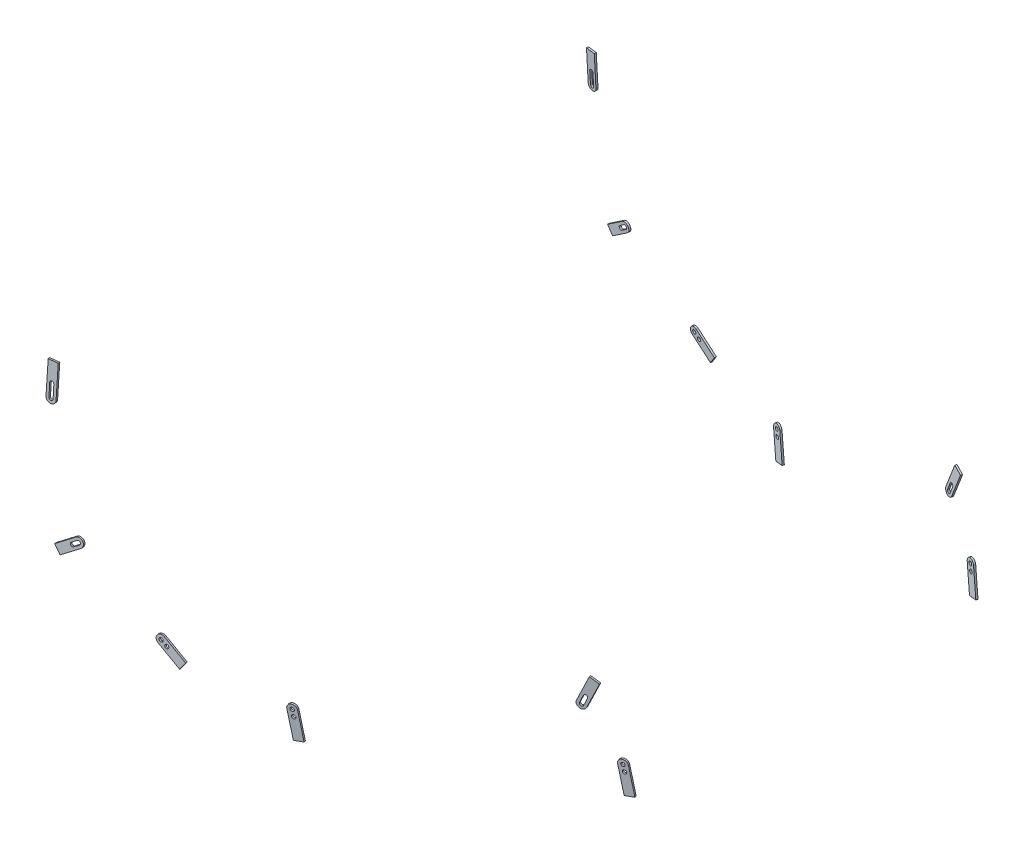
SolidWorks part; units mm, degrees
ref_plane "Front Plane" through (0, 0, 0) normal (0, 0, 1) x (1, 0, 0)
ref_plane "Top Plane" through (0, 0, 0) normal (0, 1, 0) x (1, 0, 0)
ref_plane "Right Plane" through (0, 0, 0) normal (1, 0, 0) x (0, 0, -1)
sketch3d "3DSketch1"
  line L0 (394.3882, 355.8329, 258.042) -> (773.7071, 652.4915, 190.2318) construction
  line L1 (773.7071, 652.4915, 190.2318) -> (658.3543, 555, 15) construction
  line L2 (394.3882, 355.8329, -258.042) -> (773.7071, 652.4915, -190.2318) construction
  line L3 (773.7071, 652.4915, -190.2318) -> (658.3543, 555, -15) construction
  line L4 (773.7071, 349.9436, 210) -> (-11.91, 362.141, 309.501) construction
  line L5 (-163, 610, 200) -> (-87.4986, 741.4827, 256.6073) construction
  line L6 (-68.7898, 625.9945, -300.6274) -> (-163, 610, -200) construction
  line L7 (-68.7898, 625.9945, 300.6274) -> (-68.7898, 625.9945, -300.6274) construction
  line L8 (-68.7898, 625.9945, 300.6274) -> (-163, 610, 200) construction
  line L9 (-163, 610, 200) -> (-163, 610, -200) construction
  line L10 (-163, 610, 200) -> (-163, 610, 230) construction
  line L11 (773.7071, 349.9436, -210) -> (-11.91, 362.141, -309.501) construction
  line L12 (-163, 610, -200) -> (-87.4986, 741.4827, -256.6073) construction
  line L13 (-163, 610, -200) -> (-163, 610, -230) construction
  line L14 (773.7071, 180, 150) -> (394.3882, 355.8329, 258.042) construction
  line L15 (200, 72.7, 300) -> (773.7071, 180, 150) construction
  line L16 (200, 72.7, 300) -> (394.3882, 355.8329, 258.042) construction
  line L17 (200, 72.7, -300) -> (394.3882, 355.8329, -258.042) construction
  line L18 (200, 72.7, -300) -> (773.7071, 180, -150) construction
  line L19 (773.7071, 180, -150) -> (394.3882, 355.8329, -258.042) construction
  line L20 (-100.891, 824.1527, 220.3063) -> (-100.891, 824.1527, -220.3063) construction
  line L21 (-176.299, 812.9937, 150) -> (-100.891, 824.1527, 220.3063) construction
  line L22 (-176.299, 812.9937, 150) -> (-176.299, 812.9937, -150) construction
  line L23 (-176.299, 812.9937, -150) -> (-100.891, 824.1527, -220.3063) construction
  line L24 (394.3882, 355.8329, 258.042) -> (773.7071, 652.4915, 190.2318)
  line L25 (773.7071, 652.4915, 190.2318) -> (658.3543, 555, 15)
  line L26 (394.3882, 355.8329, -258.042) -> (773.7071, 652.4915, -190.2318)
  line L27 (773.7071, 652.4915, -190.2318) -> (658.3543, 555, -15)
  line L28 (773.7071, 349.9436, 210) -> (-11.91, 362.141, 309.501)
  line L29 (-163, 610, 200) -> (-87.4986, 741.4827, 256.6073)
  line L30 (-68.7898, 625.9945, -300.6274) -> (-163, 610, -200)
  line L31 (-68.7898, 625.9945, 300.6274) -> (-68.7898, 625.9945, -300.6274)
  line L32 (-68.7898, 625.9945, 300.6274) -> (-163, 610, 200)
  line L33 (-163, 610, 200) -> (-163, 610, -200)
  line L34 (-163, 610, 200) -> (-163, 610, 230)
  line L35 (773.7071, 349.9436, -210) -> (-11.91, 362.141, -309.501)
  line L36 (-163, 610, -200) -> (-87.4986, 741.4827, -256.6073)
  line L37 (-163, 610, -200) -> (-163, 610, -230)
  line L38 (773.7071, 180, 150) -> (394.3882, 355.8329, 258.042)
  line L39 (200, 72.7, 300) -> (773.7071, 180, 150)
  line L40 (200, 72.7, 300) -> (394.3882, 355.8329, 258.042)
  line L41 (200, 72.7, -300) -> (394.3882, 355.8329, -258.042)
  line L42 (200, 72.7, -300) -> (773.7071, 180, -150)
  line L43 (773.7071, 180, -150) -> (394.3882, 355.8329, -258.042)
  line L44 (-100.891, 824.1527, 220.3063) -> (-100.891, 824.1527, -220.3063)
  line L45 (-176.299, 812.9937, 150) -> (-100.891, 824.1527, 220.3063)
  line L46 (-176.299, 812.9937, 150) -> (-176.299, 812.9937, -150)
  line L47 (-176.299, 812.9937, -150) -> (-100.891, 824.1527, -220.3063)
  line L55 (-73.9745, 657.9992, 293.2655) -> (-155.0878, 1158.7068, 73.4012)
  line L56 (-155.0878, 1158.7068, -73.4012) -> (-73.974, 657.9958, -293.267)
  line L57 (-68.7898, 625.9945, -300.6274) -> (-33.9944, 411.2044, -308.7922)
  line L58 (-19.7504, 376.8627, -309.0481) -> (200, 72.7, -300)
  line L59 (200, 72.7, -300) -> (200, 72.7, 300)
  line L60 (200, 72.7, 300) -> (-19.7504, 376.8626, 309.0481)
  line L61 (-33.9944, 411.2044, 308.7921) -> (-68.7905, 625.9984, 300.6259)
  line L62 (-73.9745, 657.9992, 293.2655) -> (-155.0878, 1158.7068, 73.4012)
  line L63 (-155.0878, 1158.7068, -73.4012) -> (-73.974, 657.9958, -293.267)
  line L64 (-68.7898, 625.9945, -300.6274) -> (-33.9944, 411.2044, -308.7922)
  line L65 (-19.7504, 376.8627, -309.0481) -> (200, 72.7, -300)
  line L66 (200, 72.7, -300) -> (200, 72.7, 300)
  line L67 (200, 72.7, 300) -> (-19.7504, 376.8626, 309.0481)
  line L68 (-33.9944, 411.2044, 308.7921) -> (-68.7905, 625.9984, 300.6259)
  arc A5 (-155.0878, 1158.7068, 73.4012) -> (-155.0878, 1158.7068, -73.4012) centre (-150, 1127.3, 0) ccw
  arc A6 (-73.974, 657.9958, -293.267) -> (-68.7898, 625.9945, -300.6274) centre (-68.2502, 622.6632, -210.6907) ccw
  arc A7 (-33.9944, 411.2044, -308.7922) -> (-19.7504, 376.8627, -309.0481) centre (44.3936, 423.5158, -298.6062) ccw
  arc A8 (-19.7504, 376.8626, 309.0481) -> (-33.9944, 411.2044, 308.7921) centre (44.3935, 423.5157, 298.6052) ccw
  arc A9 (-68.7905, 625.9984, 300.6259) -> (-73.9745, 657.9992, 293.2655) centre (-68.2507, 622.6666, 210.6892) ccw
  arc A10 (-155.0878, 1158.7068, 73.4012) -> (-155.0878, 1158.7068, -73.4012) centre (-150, 1127.3, 0) ccw
  arc A11 (-73.974, 657.9958, -293.267) -> (-68.7898, 625.9945, -300.6274) centre (-68.2502, 622.6632, -210.6907) ccw
  arc A12 (-33.9944, 411.2044, -308.7922) -> (-19.7504, 376.8627, -309.0481) centre (44.3936, 423.5158, -298.6062) ccw
  arc A13 (-19.7504, 376.8626, 309.0481) -> (-33.9944, 411.2044, 308.7921) centre (44.3935, 423.5157, 298.6052) ccw
  arc A14 (-68.7905, 625.9984, 300.6259) -> (-73.9745, 657.9992, 293.2655) centre (-68.2507, 622.6666, 210.6892) ccw
  point P15 (312.3652, 236.3637, -275.7464)
  point P19 (342.8028, 99.4083, -262.6632)
  point P26 (-228.9705, 1114.507, 0)
  point P36 (-157.092, 608.271, -210.6907)
  point P49 (34.8074, 418.9488, -219.314)
  point P52 (34.8065, 418.9481, 219.3131)
  point P59 (-157.0925, 608.2744, 210.6892)
  point P61 (-228.9705, 1114.507, 0)
  point P62 (-157.092, 608.271, -210.6907)
  point P64 (34.8074, 418.9488, -219.314)
  point P65 (34.8065, 418.9481, 219.3131)
  point P66 (-157.0925, 608.2744, 210.6892)
  dimension "D2" = 200
  dimension "D3" = 150
  dimension "D1" = 0
ref_plane "Plane2" through (41.2728, 19.5993, -323.47) normal (0.1263, 0.06, -0.9902) x (-0.992, 0.0076, -0.1261)
sketch "Sketch1" plane through (41.2728, 19.5993, -323.47) normal (0.1263, 0.06, -0.9902) x (-0.992, 0.0076, -0.1261)
  line L0 (-180.2345, 131.5264) -> (-202.4867, 116.2346) construction
  line L1 (-66.3875, 341.8265) -> (-56.3875, 341.9043)
  line L6 (-66.3875, 341.8265) -> (-66.1154, 306.8265)
  line L7 (-56.3875, 341.9043) -> (-56.1154, 306.9043)
  line L9 (-738.3507, 336.6022) -> (53.6125, 342.7595) construction
  line L10 (-205.3185, 120.3553) -> (-199.6548, 112.1138)
  line L11 (-205.3185, 120.3553) -> (-183.0663, 135.6472)
  line L12 (-199.6548, 112.1138) -> (-177.4027, 127.4056)
  line L14 (-160.0093, 54.423) -> (-355.9677, 339.5751) construction
  circle A0 centre (-61.1154, 306.8654) radius 2.05
  circle A1 centre (-61.1154, 313.8654) radius 2.05
  circle A2 centre (-61.1154, 320.8654) radius 2.05
  arc A3 (-56.1154, 306.9043) -> (-66.1154, 306.8265) centre (-61.1154, 306.8654) cw
  arc A4 (-183.0663, 135.6472) -> (-177.4027, 127.4056) centre (-180.2345, 131.5264) cw
  circle A5 centre (-180.2345, 131.5264) radius 2.05
  circle A6 centre (-186.0036, 127.5619) radius 2.05
  dimension "D5" = 4.1
  dimension "D10" = 4.1
  dimension "D1" = 10
  dimension "D2" = 110
  dimension "D3" = 35
  dimension "D4" = 7
  dimension "D6" = 7
  dimension "D7" = 27
  dimension "D8" = 10
  dimension "D9" = 70
  dimension "D11" = 7
ref_plane "Plane3" through (41.6519, 19.7793, -326.4406) normal (0.1263, 0.06, -0.9902) x (-0.992, 0.0076, -0.1261)
sketch "Sketch2" plane through (41.6519, 19.7793, -326.4406) normal (0.1263, 0.06, -0.9902) x (-0.992, 0.0076, -0.1261)
  line L0 (-94.9128, 185.88) -> (-89.261, 181.75) construction
  line L1 (-77.6776, 167.0931) -> (-71.7777, 175.1671)
  line L2 (-77.6776, 167.0931) -> (-97.8628, 181.843)
  line L3 (-56.3875, 341.9043) -> (-66.3875, 341.8265)
  line L4 (-56.1154, 306.9043) -> (-56.3875, 341.9043)
  line L5 (-66.3875, 341.8265) -> (-66.1154, 306.8265)
  line L6 (-56.3875, 341.9043) -> (-66.3875, 341.8265)
  line L7 (-56.1154, 306.9043) -> (-56.3875, 341.9043)
  line L8 (-66.3875, 341.8265) -> (-66.1154, 306.8265)
  line L9 (-205.3185, 120.3553) -> (-199.6548, 112.1138)
  line L10 (-183.0663, 135.6472) -> (-205.3185, 120.3553)
  line L11 (-199.6548, 112.1138) -> (-177.4027, 127.4056)
  line L12 (-205.3185, 120.3553) -> (-199.6548, 112.1138)
  line L13 (-183.0663, 135.6472) -> (-205.3185, 120.3553)
  line L14 (-199.6548, 112.1138) -> (-177.4027, 127.4056)
  line L15 (-71.7777, 175.1671) -> (-91.9628, 189.917)
  line L17 (61.4454, 357.4816) -> (-160.0093, 54.423) construction
  line L18 (-94.9128, 185.88) -> (-74.7277, 171.1301) construction
  line L21 (-94.9128, 185.88) -> (-89.261, 181.75) construction
  line L22 (-93.7033, 187.5352) -> (-88.0515, 183.4052)
  line L23 (-96.1223, 184.2248) -> (-90.4704, 180.0948)
  line L24 (-61.1154, 320.8654) -> (-61.1154, 313.8654) construction
  line L25 (-61.1154, 313.8654) -> (-61.1154, 306.8654) construction
  line L26 (-61.1154, 320.8654) -> (-61.1154, 306.8654) construction
  line L27 (-59.0654, 320.8654) -> (-59.0654, 306.8654)
  line L28 (-63.1654, 320.8654) -> (-63.1654, 306.8654)
  arc A0 (-91.9628, 189.917) -> (-97.8628, 181.843) centre (-94.9128, 185.88) ccw
  arc A1 (-59.0654, 320.8654) -> (-63.1654, 320.8654) centre (-61.1154, 320.8654) ccw
  arc A3 (-63.1654, 306.8654) -> (-59.0654, 306.8654) centre (-61.1154, 306.8654) ccw
  arc A7 (-66.1154, 306.8265) -> (-56.1154, 306.9043) centre (-61.1154, 306.8654) ccw
  arc A8 (-66.1154, 306.8265) -> (-56.1154, 306.9043) centre (-61.1154, 306.8654) ccw
  circle A9 centre (-186.0036, 127.5619) radius 2.05
  circle A10 centre (-186.0036, 127.5619) radius 2.05
  circle A11 centre (-180.2345, 131.5264) radius 2.05
  circle A12 centre (-180.2345, 131.5264) radius 2.05
  arc A13 (-177.4027, 127.4056) -> (-183.0663, 135.6472) centre (-180.2345, 131.5264) ccw
  arc A14 (-177.4027, 127.4056) -> (-183.0663, 135.6472) centre (-180.2345, 131.5264) ccw
  arc A19 (-93.7033, 187.5352) -> (-96.1223, 184.2248) centre (-94.9128, 185.88) ccw
  arc A20 (-90.4704, 180.0948) -> (-88.0515, 183.4052) centre (-89.261, 181.75) ccw
  point P3 (-61.1154, 313.8654)
  point P30 (-92.0869, 183.815)
  point P36 (-92.0869, 183.815)
  dimension "D10" = 4.1
  dimension "D8" = 10
  dimension "D9" = 25
  dimension "D11" = 7
  dimension "D2" = 4.1
  dimension "D4" = 0
  dimension "D5" = 0
  dimension "D6" = 0
  dimension "D7" = 0
ref_plane "Plane4" through (39.0839, 18.5598, -306.3145) normal (0.1263, 0.06, -0.9902) x (-0.992, 0.0076, -0.1261)
sketch "Sketch4" plane through (39.0839, 18.5598, -306.3145) normal (0.1263, 0.06, -0.9902) x (-0.992, 0.0076, -0.1261)
  line L0 (-311.0771, 84.3109) -> (-301.2673, 82.3701)
  line L1 (-311.0771, 84.3109) -> (-305.2547, 113.7404)
  line L2 (-301.2673, 82.3701) -> (-295.4448, 111.7996)
  line L4 (-160.0093, 54.423) -> (-747.2158, 170.5985) construction
  line L5 (-300.3497, 112.77) -> (-306.1722, 83.3405) construction
  arc A0 (-295.4448, 111.7996) -> (-305.2547, 113.7404) centre (-300.3497, 112.77) ccw
  circle A1 centre (-300.3497, 112.77) radius 2.05
  circle A2 centre (-301.7083, 105.9031) radius 2.05
  dimension "D4" = 4.1
  dimension "D1" = 10
  dimension "D2" = 30
  dimension "D3" = 5
  dimension "D5" = 7
extrude "Boss-Extrude4" add sketch "Sketch2" along normal blind 2 separate body
ref_plane "Plane6" through (87.7148, -11.7513, -327.0781) normal (-0.2589, 0.0347, 0.9653) x (0.9659, 0.0093, 0.2587)
ref_plane "Plane5" through (88.7503, -11.89, -330.9393) normal (-0.2589, 0.0347, 0.9653) x (0.9659, 0.0093, 0.2587)
sketch "Sketch5" plane through (88.7503, -11.89, -330.9393) normal (-0.2589, 0.0347, 0.9653) x (0.9659, 0.0093, 0.2587)
  line L0 (571.2295, 161.4402) -> (561.3733, 159.7502)
  line L1 (571.2295, 161.4402) -> (566.1594, 191.0087)
  line L2 (561.3733, 159.7502) -> (556.3032, 189.3187)
  line L4 (116.2477, 83.4246) -> (710.2012, 185.2697) construction
  line L5 (561.2313, 190.1637) -> (566.3014, 160.5952) construction
  line L6 (269.121, 109.6378) -> (259.2649, 107.9477)
  line L7 (269.121, 109.6378) -> (264.0509, 139.2062)
  line L8 (259.2649, 107.9477) -> (254.1948, 137.5162)
  line L10 (259.1229, 138.3612) -> (264.0901, 108.7751) construction
  line L11 (541.9608, 262.2123) -> (532.8667, 266.3713)
  line L12 (541.9608, 262.2123) -> (529.4836, 234.9301)
  line L13 (532.8667, 266.3713) -> (520.3896, 239.0891)
  line L15 (537.4138, 264.2918) -> (524.9366, 237.0096) construction
  line L16 (524.9366, 237.0096) -> (528.6798, 245.1942) construction
  line L17 (523.0723, 237.8622) -> (526.8155, 246.0469)
  line L18 (526.8009, 236.157) -> (530.544, 244.3416)
  line L19 (710.2012, 185.2697) -> (317.496, 364.8684) construction
  arc A0 (556.3032, 189.3187) -> (566.1594, 191.0087) centre (561.2313, 190.1637) cw
  circle A1 centre (561.2313, 190.1637) radius 2.05
  circle A2 centre (562.4143, 183.2644) radius 2.05
  arc A3 (254.1948, 137.5162) -> (264.0509, 139.2062) centre (259.1229, 138.3612) cw
  circle A4 centre (259.1229, 138.3612) radius 2.05
  circle A5 centre (260.2819, 131.4578) radius 2.05
  arc A6 (520.3896, 239.0891) -> (529.4836, 234.9301) centre (524.9366, 237.0096) ccw
  arc A8 (523.0723, 237.8622) -> (526.8009, 236.157) centre (524.9366, 237.0096) ccw
  arc A9 (530.544, 244.3416) -> (526.8155, 246.0469) centre (528.6798, 245.1942) ccw
  point P28 (526.8082, 241.1019)
  dimension "D3" = 4.1
  dimension "D7" = 4.1
  dimension "D13" = 4.1
  dimension "D1" = 10
  dimension "D2" = 30
  dimension "D4" = 7
  dimension "D5" = 30
  dimension "D6" = 10
  dimension "D8" = 7
  dimension "D9" = 10
  dimension "D10" = 141
  dimension "D11" = 185
  dimension "D12" = 30
  dimension "D14" = 9
extrude "Boss-Extrude5" add sketch "Sketch5" against normal blind 2 separate body
mirror "Mirror3" about plane through (0, 0, 0) normal (0, 0, 1) of bodies 111 109 110 107 112 113
